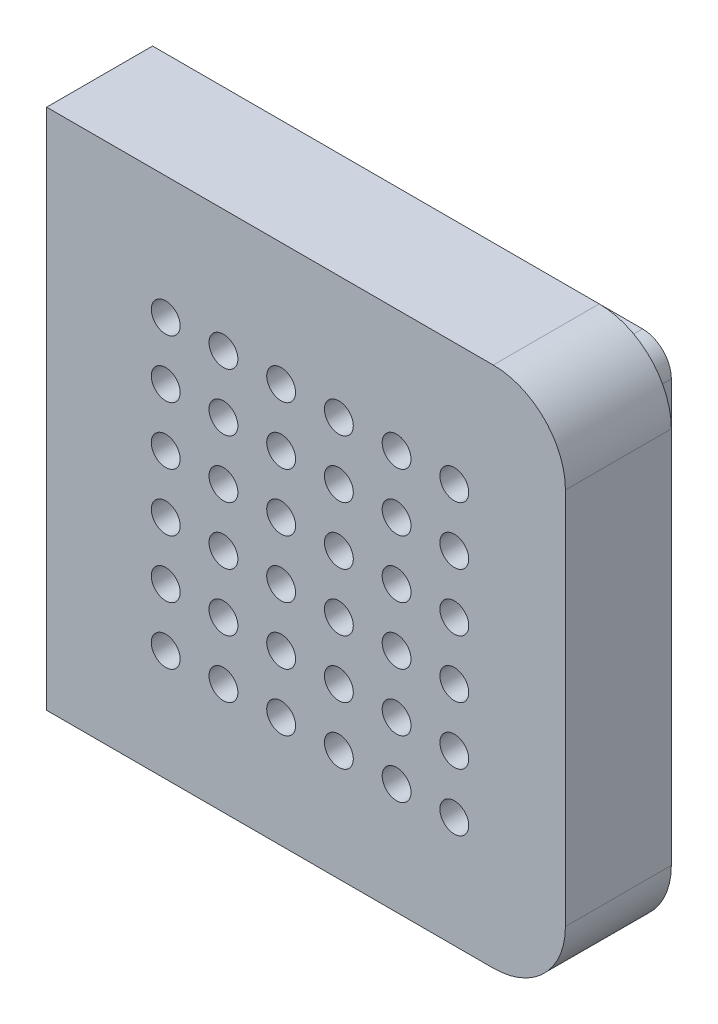
SolidWorks part; units mm, degrees
ref_plane "Front Plane" through (0, 0, 0) normal (0, 0, 1) x (1, 0, 0)
ref_plane "Top Plane" through (0, 0, 0) normal (0, 1, 0) x (1, 0, 0)
ref_plane "Right Plane" through (0, 0, 0) normal (1, 0, 0) x (0, 0, -1)
sketch "Sketch1" plane through (0, 0, 0) normal (0, 0, 1) x (1, 0, 0)
  line L1 (-7.8, 9.05) -> (7.8, 9.05)
  line L2 (-7.8, 9.05) -> (-7.8, -9.05)
  line L3 (-7.8, -9.05) -> (7.8, -9.05)
  line L4 (10.3, 6.55) -> (10.3, -6.55)
  arc A0 (7.8, 9.05) -> (10.3, 6.55) centre (7.8, 6.55) cw
  arc A1 (7.8, -9.05) -> (10.3, -6.55) centre (7.8, -6.55) ccw
  point P10 (10.3, 9.05)
  dimension "D1" = 18.1
  dimension "D2" = 18.1
extrude "Boss-Extrude1" add sketch "Sketch1" along normal blind 3.67
sketch "Sketch6" plane through (0, 0, 3.67) normal (0, 0, 1) x (1, 0, 0)
  line L4 (-4.8, 6.05) -> (-4.8, -6.05) construction
  line L5 (-4.8, -6.05) -> (7.3, -6.05) construction
  line L14 (7.3, -6.05) -> (7.3, 6.05) construction
  line L15 (7.3, 6.05) -> (-4.8, 6.05) construction
  line L16 (-4.8, 4.8) -> (-3.55, 4.8) construction
  line L17 (-3.55, 4.8) -> (-3.55, 6.05) construction
  circle A128 centre (-3.55, 4.8) radius 0.5
  circle A129 centre (-1.55, 4.8) radius 0.5
  circle A130 centre (0.45, 4.8) radius 0.5
  circle A131 centre (2.45, 4.8) radius 0.5
  circle A132 centre (4.45, 4.8) radius 0.5
  circle A133 centre (6.45, 4.8) radius 0.5
  circle A134 centre (-1.55, 2.8) radius 0.5
  circle A135 centre (0.45, 2.8) radius 0.5
  circle A136 centre (2.45, 2.8) radius 0.5
  circle A137 centre (4.45, 2.8) radius 0.5
  circle A138 centre (6.45, 2.8) radius 0.5
  circle A139 centre (-1.55, 0.8) radius 0.5
  circle A140 centre (0.45, 0.8) radius 0.5
  circle A141 centre (2.45, 0.8) radius 0.5
  circle A142 centre (4.45, 0.8) radius 0.5
  circle A143 centre (6.45, 0.8) radius 0.5
  circle A144 centre (-1.55, -1.2) radius 0.5
  circle A145 centre (0.45, -1.2) radius 0.5
  circle A146 centre (2.45, -1.2) radius 0.5
  circle A147 centre (4.45, -1.2) radius 0.5
  circle A148 centre (6.45, -1.2) radius 0.5
  circle A149 centre (-1.55, -3.2) radius 0.5
  circle A150 centre (0.45, -3.2) radius 0.5
  circle A151 centre (2.45, -3.2) radius 0.5
  circle A152 centre (4.45, -3.2) radius 0.5
  circle A153 centre (6.45, -3.2) radius 0.5
  circle A154 centre (-1.55, -5.2) radius 0.5
  circle A155 centre (0.45, -5.2) radius 0.5
  circle A156 centre (2.45, -5.2) radius 0.5
  circle A157 centre (4.45, -5.2) radius 0.5
  circle A158 centre (6.45, -5.2) radius 0.5
  circle A159 centre (-3.55, 2.8) radius 0.5
  circle A160 centre (-3.55, 0.8) radius 0.5
  circle A161 centre (-3.55, -1.2) radius 0.5
  circle A162 centre (-3.55, -3.2) radius 0.5
  circle A163 centre (-3.55, -5.2) radius 0.5
  dimension "D4" = 1.25
  dimension "D6" = 1
  dimension "D5" = 1.25
extrude "Cut-Extrude1" cut sketch "Sketch6" against normal up to surface (3.67 mm away) up to face at (3.6059, 0, 0)
sketch "Sketch20" plane through (0, 0, 0) normal (0, 0, -1) x (-1, 0, 0)
  line L0 (4.8, -6.05) -> (4.8, 6.05)
  line L1 (4.8, 6.05) -> (-7.3, 6.05)
  line L2 (-7.3, 6.05) -> (-7.3, -6.05)
  line L3 (-7.3, -6.05) -> (4.8, -6.05)
  line L22 (6.3, -7.55) -> (6.3, 7.55)
  line L59 (6.3, 7.55) -> (-7.8, 7.55)
  line L60 (-8.8, 6.55) -> (-8.8, -6.55)
  line L61 (-7.8, -7.55) -> (6.3, -7.55)
  arc A0 (-7.3, 6.05) -> (-7.3, 6.05) centre (-7.3, 6.05) ccw
  arc A1 (-7.3, -6.05) -> (-7.3, -6.05) centre (-7.3, -6.05) ccw
  arc A10 (-7.8, 7.55) -> (-8.8, 6.55) centre (-7.8, 6.55) ccw
  arc A11 (-8.8, -6.55) -> (-7.8, -7.55) centre (-7.8, -6.55) ccw
  dimension "D1" = 1.5
extrude "Boss-Extrude4" add sketch "Sketch20" along normal blind 1.5
sketch "Sketch13" plane through (0, -9.05, 0) normal (0, -1, 0) x (1, 0, 0)
  line L0 (0, 0) -> (0, 3.67) construction
  line L1 (-7.8, 0) -> (7.8, 0) construction
  line L2 (-7.8, 3.67) -> (7.8, 3.67) construction
  line L3 (-5, 0.5) -> (5, 0.5) construction
  line L4 (-6, 0) -> (-5, 0)
  line L5 (-6, 0) -> (-6, 0.5)
  line L6 (-6, 0.5) -> (-5, 0.5)
  line L7 (-5, 0) -> (-5, 0.5)
  line L8 (5, 0) -> (6, 0)
  line L9 (5, 0) -> (5, 0.5)
  line L10 (5, 0.5) -> (6, 0.5)
  line L11 (6, 0) -> (6, 0.5)
  point P14 (0, 0.5)
  dimension "D1" = 0.5
  dimension "D2" = 1
  dimension "D3" = 1
  dimension "D4" = 10
extrude "Cut-Extrude7" cut sketch "Sketch13" against normal blind 0.5
sketch "Sketch14" plane through (-6, 0, 0) normal (1, 0, 0) x (0, 0, -1)
  line L0 (-0.25, -8.8) -> (-0.25, -9.05) construction
  line L2 (-0.25, -8.8) -> (0, -8.8) construction
  line L3 (0, -8.55) -> (0, -9.05) construction
  line L4 (-0.5, -9.05) -> (0, -9.05) construction
  circle A0 centre (-0.25, -8.8) radius 0.125
  dimension "D1" = 0.25
extrude "Cut-Extrude8" cut sketch "Sketch14" against normal blind 0.25
sketch "Sketch15" plane through (-5, 0, 0) normal (-1, 0, 0) x (0, 0, 1)
  circle A1 centre (0.25, -8.8) radius 0.125
  circle A2 centre (0.25, -8.8) radius 0.125
  dimension "D1" = 0
extrude "Cut-Extrude9" cut sketch "Sketch15" against normal blind 0.25
sketch "Sketch16" plane through (6, 0, 0) normal (-1, 0, 0) x (0, 0, 1)
  circle A1 centre (0.25, -8.8) radius 0.125
  circle A2 centre (0.25, -8.8) radius 0.125
  dimension "D1" = 0
extrude "Cut-Extrude10" cut sketch "Sketch16" against normal blind 0.25
sketch "Sketch17" plane through (5, 0, 0) normal (1, 0, 0) x (0, 0, -1)
  circle A1 centre (-0.25, -8.8) radius 0.125
  circle A2 centre (-0.25, -8.8) radius 0.125
  dimension "D1" = 0
extrude "Cut-Extrude11" cut sketch "Sketch17" against normal blind 0.25
sketch "Sketch19" plane through (-7.8, 0, 0) normal (-1, 0, 0) x (0, 0, 1)
  line L4 (0, 9.05) -> (0, -9.05)
  line L5 (0, -9.05) -> (3.67, -9.05)
  line L6 (3.67, -9.05) -> (3.67, 9.05)
  line L7 (3.67, 9.05) -> (0, 9.05)
  line L8 (0, 9.05) -> (0, -9.05)
  line L9 (0, -9.05) -> (3.67, -9.05)
  line L10 (3.67, -9.05) -> (3.67, 9.05)
  line L11 (3.67, 9.05) -> (0, 9.05)
  dimension "D1" = 0
extrude "Cut-Extrude13" cut sketch "Sketch19" against normal blind 0.125
sketch "Sketch21" plane through (-7.675, 0, 0) normal (-1, 0, 0) x (0, 0, 1)
  line L0 (0, -8.55) -> (0, -9.05)
  line L1 (0, -9.05) -> (0.5, -9.05)
  line L2 (0, -9.05) -> (3.67, -9.05) construction
  arc A0 (0.5, -9.05) -> (0, -8.55) centre (0.5, -8.55) cw
  dimension "D1" = 0.5
extrude "Cut-Extrude14" cut sketch "Sketch21" against normal up to surface (15.475 mm away)
